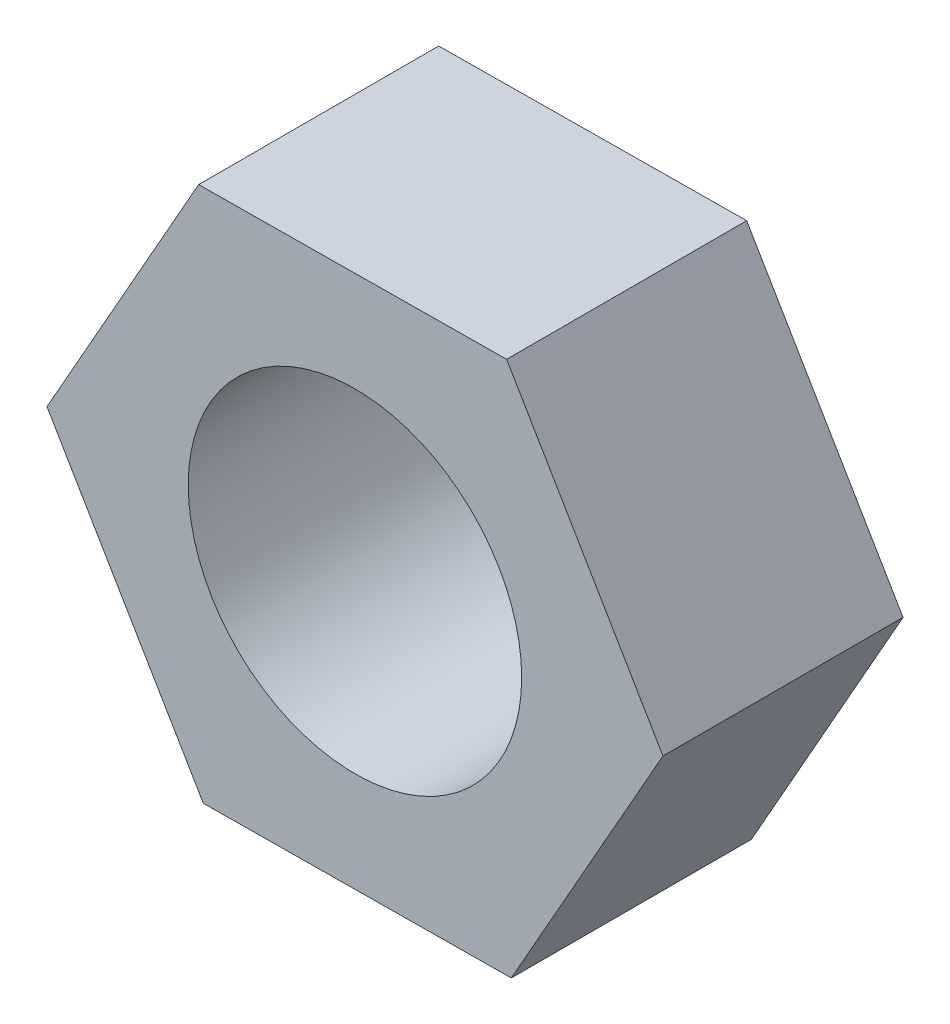
SolidWorks part; units mm, degrees
ref_plane "前视基准面" through (0, 0, 0) normal (0, 0, 1) x (1, 0, 0)
ref_plane "上视基准面" through (0, 0, 0) normal (0, 1, 0) x (1, 0, 0)
ref_plane "右视基准面" through (0, 0, 0) normal (1, 0, 0) x (0, 0, -1)
sketch "草图1" plane through (0, 0, 0) normal (0, 0, 1) x (1, 0, 0)
  line L1 (2.3445, -3.9795) -> (4.6186, 0.0407)
  line L2 (4.6186, 0.0407) -> (2.2741, 4.0202)
  line L3 (2.2741, 4.0202) -> (-2.3445, 3.9795)
  line L4 (-2.3445, 3.9795) -> (-4.6186, -0.0407)
  line L5 (-4.6186, -0.0407) -> (-2.2741, -4.0202)
  line L6 (-2.2741, -4.0202) -> (2.3445, -3.9795)
  circle A0 centre (0, 0) radius 4 construction
  circle A1 centre (0, 0) radius 2.5
extrude "凸台-拉伸1" add sketch "草图1" along normal blind 3.6
